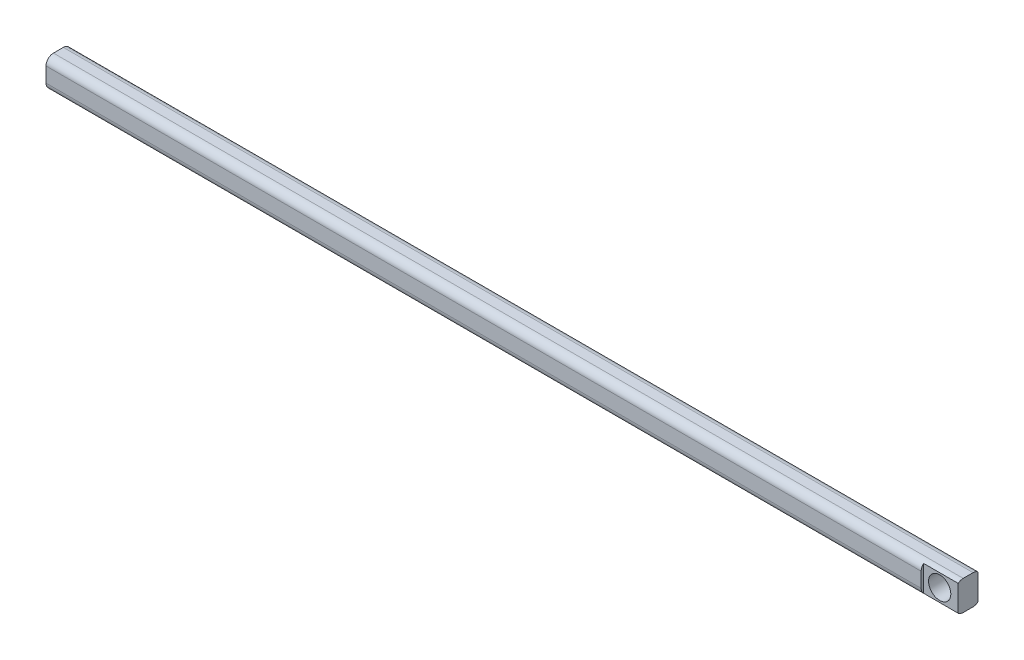
SolidWorks part; units mm, degrees
material "Acero inoxidable al cromo"
ref_plane "Front" through (0, 0, 0) normal (0, 0, 1) x (1, 0, 0)
ref_plane "Top" through (0, 0, 0) normal (0, 1, 0) x (1, 0, 0)
ref_plane "Right" through (0, 0, 0) normal (1, 0, 0) x (0, 0, -1)
sketch "Croquis1" plane through (0, 0, 0) normal (0, 0, 1) x (1, 0, 0)
  line L2 (-18.75, -15) -> (18.75, -15)
  line L3 (-18.75, -15) -> (-18.75, 15)
  line L4 (-18.75, 15) -> (18.75, 15)
  line L5 (18.75, -15) -> (18.75, 15)
  line L6 (-18.75, -15) -> (18.75, 15) construction
  line L7 (-18.75, 15) -> (18.75, -15) construction
  point P1 (0, 0)
  dimension "D1" = 37.5
  dimension "D2" = 30
extrude "Saliente-Extruir1" add sketch "Croquis1" along normal blind 15
sketch "Croquis2" plane through (0, 0, 0) normal (0, 0, 1) x (1, 0, 0)
  line L0 (-18.75, 15) -> (-18.75, -15) construction
  line L1 (-18.75, 3.7) -> (-26.75, 3.7)
  line L2 (-18.75, 3.7) -> (-18.75, -3.7)
  line L3 (-18.75, -3.7) -> (-26.75, -3.7)
  line L4 (-27.75, 2.7) -> (-27.75, -2.7)
  line L5 (0, 0) -> (-15.2309, 0) construction
  line L6 (-27.75, 0) -> (-18.75, 0) construction
  line L7 (18.75, 15) -> (-18.75, 15) construction
  line L8 (-10, 15) -> (10, 15)
  line L9 (-10, 15) -> (-10, 24)
  line L10 (-9, 25) -> (9, 25)
  line L11 (10, 15) -> (10, 24)
  line L12 (0, 0) -> (0, -15) construction
  line L13 (-18.75, -15) -> (18.75, -15) construction
  line L14 (-9, -25) -> (9, -25)
  line L15 (10, -15) -> (10, -24)
  line L16 (-10, -15) -> (10, -15)
  line L17 (-10, -15) -> (-10, -24)
  circle A0 centre (-23.25, 0) radius 2.1
  arc A1 (-26.75, -3.7) -> (-27.75, -2.7) centre (-26.75, -2.7) cw
  arc A2 (-26.75, 3.7) -> (-27.75, 2.7) centre (-26.75, 2.7) ccw
  circle A3 centre (-5.5, 20) radius 2.1
  circle A4 centre (5.5, 20) radius 2.1
  arc A5 (9, 25) -> (10, 24) centre (9, 24) cw
  arc A6 (-10, 24) -> (-9, 25) centre (-9, 24) cw
  circle A7 centre (5.5, -20) radius 2.1
  circle A8 centre (-5.5, -20) radius 2.1
  arc A9 (9, -25) -> (10, -24) centre (9, -24) ccw
  arc A10 (-10, -24) -> (-9, -25) centre (-9, -24) ccw
  point P16 (-27.75, -3.7)
  point P19 (-27.75, 3.7)
  point P35 (10, 25)
  point P38 (-10, 25)
  dimension "D2" = 4.2
  dimension "D4" = 1
  dimension "D5" = 4.2
  dimension "D6" = 11
  dimension "D9" = 1
  dimension "D10" = 5
  dimension "D1" = 7.4
  dimension "D3" = 9
  dimension "D7" = 20
  dimension "D8" = 10
extrude "Saliente-Extruir2" add sketch "Croquis2" along normal blind 1
sketch "Croquis3" plane through (18.75, 0, 0) normal (1, 0, 0) x (0, 0, -1)
  line L0 (0, 0) -> (-15, 0) construction
  line L1 (-15, -15) -> (-15, 15) construction
  line L2 (0, -15) -> (0, 15) construction
  line L3 (-10.5, -12.5) -> (-4.5, -12.5)
  line L4 (-13.5, -9.5) -> (-13.5, 9.5)
  line L5 (-10.5, 12.5) -> (-4.5, 12.5)
  line L6 (-1.5, -9.5) -> (-1.5, 9.5)
  line L7 (-13.5, -12.5) -> (-1.5, 12.5) construction
  line L8 (-13.5, 12.5) -> (-1.5, -12.5) construction
  arc A0 (-10.5, -12.5) -> (-13.5, -9.5) centre (-10.5, -9.5) cw
  arc A1 (-4.5, -12.5) -> (-1.5, -9.5) centre (-4.5, -9.5) ccw
  arc A2 (-4.5, 12.5) -> (-1.5, 9.5) centre (-4.5, 9.5) cw
  arc A3 (-13.5, 9.5) -> (-10.5, 12.5) centre (-10.5, 9.5) cw
  point P5 (-7.5, 0)
  dimension "D3" = 3
  dimension "D1" = 1.5
  dimension "D2" = 25
sketch "Croquis4" plane through (0, 0, 15) normal (0, 0, 1) x (1, 0, 0)
  line L0 (-23.25, 0) -> (64.25, 0) construction
  dimension "D1" = 87.5
extrude "Saliente-Extruir3" add sketch "Croquis3" along normal blind 35
ref_plane "Plano1" through (0, 0, 7.5) normal (0, 0, 1) x (1, 0, 0)
sketch "Croquis5" plane through (0, 0, 7.5) normal (0, 0, 1) x (1, 0, 0)
  line L14 (-23.25, 0) -> (64.25, 0) construction
  line L15 (53.75, 6) -> (71.75, 6)
  line L16 (53.75, 9.5) -> (53.75, -9.5) construction
  line L17 (71.75, 6) -> (71.75, -6)
  line L18 (71.75, -6) -> (53.75, -6)
  line L19 (53.75, -6) -> (53.75, 6)
  circle A1 centre (64.25, 0) radius 4.5
  dimension "D1" = 12
  dimension "D2" = 6
  dimension "9" = 9
  dimension "D3" = 18
extrude "Saliente-Extruir4" add sketch "Croquis5" along normal mid plane 10
sketch "Croquis6" plane through (71.75, 0, 0) normal (1, 0, 0) x (0, 0, -1)
  line L0 (-11.5, 6) -> (-11.5, -6)
  line L1 (-12.5, 6) -> (-2.5, 6) construction
  line L2 (-12.5, -6) -> (-2.5, -6) construction
  line L3 (-3.5, 6) -> (-3.5, -6)
  line L4 (-12.5, 6) -> (-2.5, 6) construction
  line L5 (-12.5, -6) -> (-2.5, -6) construction
  line L6 (-12.5, -6) -> (-12.5, 6) construction
  line L7 (-2.5, -6) -> (-2.5, 6) construction
  line L8 (-3.5, -6) -> (-2.5, -6)
  line L9 (-11.5, 6) -> (-12.5, 6)
  line L12 (-2.5, -6) -> (-2.5, 6)
  line L13 (-2.5, 6) -> (-12.5, 6)
  line L14 (-12.5, 6) -> (-12.5, -6)
  line L15 (-12.5, -6) -> (-2.5, -6)
  line L16 (-2.5, -6) -> (-2.5, 6)
  line L17 (-2.5, 6) -> (-3.5, 6)
  line L18 (-12.5, 6) -> (-12.5, -6)
  line L19 (-12.5, -6) -> (-11.5, -6)
  dimension "D1" = 1
  dimension "D2" = 1
  dimension "D3" = 0
extrude "Cortar-Extruir2" cut sketch "Croquis6" against normal blind 14
fillet "Redondeo1" [suppressed] radius 3
fillet "Redondeo2" radius 3 4 edges at (55.75, -6, 12.5) (55.75, -6, 2.5) (55.75, 6, 2.5) (55.75, 6, 12.5)
sketch "Croquis7" plane through (0, 0, 15) normal (0, 0, 1) x (1, 0, 0)
  line L0 (53.75, 3) -> (53.75, -3) construction
  line L1 (53.75, 15) -> (77.9133, 15)
  line L2 (53.75, 15) -> (53.75, -21.2112)
  line L3 (53.75, -21.2112) -> (77.9133, -21.2112)
  line L4 (77.9133, 15) -> (77.9133, -21.2112)
extrude "Cortar-Extruir3" cut sketch "Croquis7" against normal through all and the other way through all flip side to cut
sketch "Croquis10" plane through (53.75, 0, 0) normal (-1, 0, 0) x (0, 0, 1)
  line L4 (5.5, -6) -> (9.5, -6)
  line L5 (12.5, -3) -> (12.5, 3)
  line L6 (9.5, 6) -> (5.5, 6)
  line L7 (2.5, 3) -> (2.5, -3)
  line L8 (5.5, -6) -> (9.5, -6)
  line L9 (12.5, -3) -> (12.5, 3)
  line L10 (9.5, 6) -> (5.5, 6)
  line L11 (2.5, 3) -> (2.5, -3)
  arc A4 (9.5, -6) -> (12.5, -3) centre (9.5, -3) ccw
  arc A5 (9.5, -6) -> (12.5, -3) centre (9.5, -3) ccw
  arc A6 (12.5, 3) -> (9.5, 6) centre (9.5, 3) ccw
  arc A7 (12.5, 3) -> (9.5, 6) centre (9.5, 3) ccw
  arc A12 (5.5, 6) -> (2.5, 3) centre (5.5, 3) ccw
  arc A13 (5.5, 6) -> (2.5, 3) centre (5.5, 3) ccw
  arc A14 (2.5, -3) -> (5.5, -6) centre (5.5, -3) ccw
  arc A15 (2.5, -3) -> (5.5, -6) centre (5.5, -3) ccw
  dimension "D1" = 0
extrude "Saliente-Extruir5" add sketch "Croquis10" along normal blind 350
sketch "Croquis11" plane through (-296.25, 0, 0) normal (-1, 0, 0) x (0, 0, 1)
  line L4 (5.5, -6) -> (9.5, -6)
  line L5 (12.5, -3) -> (12.5, 3)
  line L6 (9.5, 6) -> (5.5, 6)
  line L7 (2.5, 3) -> (2.5, -3)
  line L8 (5.5, -6) -> (9.5, -6)
  line L9 (12.5, -3) -> (12.5, 3)
  line L10 (9.5, 6) -> (5.5, 6)
  line L11 (2.5, 3) -> (2.5, -3)
  arc A4 (2.5, -3) -> (5.5, -6) centre (5.5, -3) ccw
  arc A5 (2.5, -3) -> (5.5, -6) centre (5.5, -3) ccw
  arc A6 (9.5, -6) -> (12.5, -3) centre (9.5, -3) ccw
  arc A7 (9.5, -6) -> (12.5, -3) centre (9.5, -3) ccw
  arc A12 (12.5, 3) -> (9.5, 6) centre (9.5, 3) ccw
  arc A13 (12.5, 3) -> (9.5, 6) centre (9.5, 3) ccw
  arc A14 (5.5, 6) -> (2.5, 3) centre (5.5, 3) ccw
  arc A15 (5.5, 6) -> (2.5, 3) centre (5.5, 3) ccw
  point P0 (7.5, -6)
  dimension "D2" = 12
  dimension "D3" = 10
  dimension "D1" = 0
